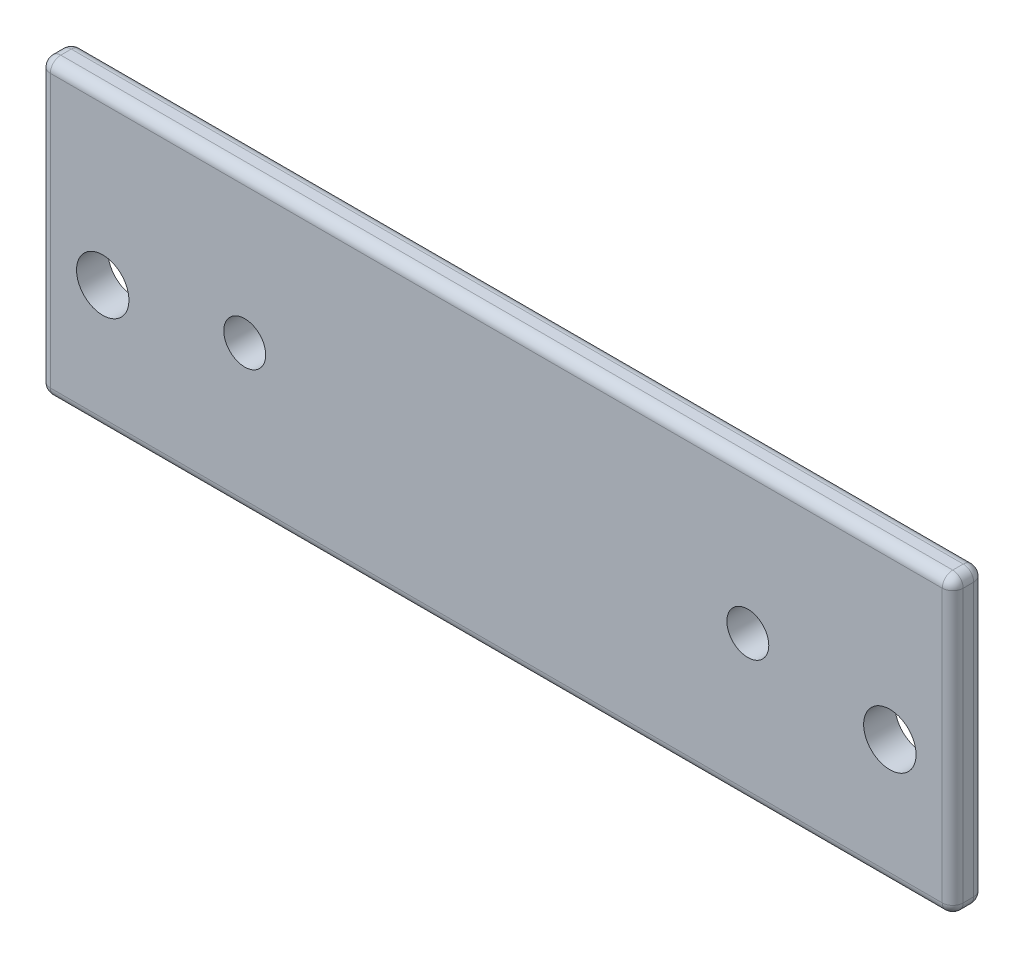
SolidWorks part; units mm, degrees
ref_plane "Front Plane" through (0, 0, 0) normal (0, 0, 1) x (1, 0, 0)
ref_plane "Top Plane" through (0, 0, 0) normal (0, 1, 0) x (1, 0, 0)
ref_plane "Right Plane" through (0, 0, 0) normal (1, 0, 0) x (0, 0, -1)
sketch "Skizze1" plane through (0, 0, 0) normal (0, 0, 1) x (1, 0, 0)
  line L0 (-37.5522, 28) -> (-43.5522, 28)
  line L1 (-37.5522, 28) -> (37.5522, 28)
  line L3 (-37.5522, 0) -> (37.5522, 0)
  line L5 (-43.5522, 28) -> (-43.5522, 0)
  line L6 (-43.5522, 0) -> (-37.5522, 0)
  line L7 (37.5522, 28) -> (43.5522, 28)
  line L8 (43.5522, 28) -> (43.5522, 0)
  line L9 (43.5522, 0) -> (37.5522, 0)
  point P11 (0, 0)
  dimension "D1" = 75.1044
  dimension "D2" = 28
  dimension "D3" = 6
extrude "Aufsatz-Linear austragen1" add sketch "Skizze1" along normal blind 3
sketch "Skizze3" plane through (0, 0, 3) normal (0, 0, 1) x (1, 0, 0)
  line L0 (-37.5522, 28) -> (-37.5522, 12) construction
  line L1 (37.5522, 28) -> (37.5522, 12) construction
  circle A0 centre (-37.5522, 12) radius 2.5
  circle A1 centre (37.5522, 12) radius 2.5
  dimension "D2" = 5
  dimension "D1" = 16
extrude "Schnitt-Linear austragen1" cut sketch "Skizze3" against normal blind 3 contours A0 | A1
sketch "Skizze4" plane through (0, 0, 0) normal (0, 1, 0) x (1, 0, 0)
  line L0 (0, -3) -> (0, -35) construction
  line L1 (43.5522, -3) -> (-43.5522, -3) construction
  line L2 (0, -35) -> (-35, -35) construction
  line L3 (-35, -35) -> (-35, -3) construction
  line L4 (-35, -3) -> (35, -3) construction
  line L5 (35, -3) -> (35, -35) construction
  line L6 (35, -35) -> (0, -35) construction
  line L7 (-24, -19) -> (0, -19) construction
  line L8 (0, -19) -> (24, -19) construction
  circle A0 centre (-24, -19) radius 2
  circle A1 centre (24, -19) radius 2
  dimension "D3" = 4
  dimension "D1" = 70
  dimension "D2" = 32
  dimension "D4" = 24
sketch "Skizze6" plane through (0, 0, 3) normal (0, 0, 1) x (1, 0, 0)
  line L0 (0, 0) -> (0, 28) construction
  line L1 (-37.5522, 0) -> (37.5522, 0) construction
  line L2 (-37.5522, 28) -> (37.5522, 28) construction
  line L3 (0, 14) -> (-24, 14) construction
  line L4 (0, 14) -> (24, 14) construction
  circle A0 centre (-24, 14) radius 2
  circle A1 centre (24, 14) radius 2
  dimension "D1" = 4
  dimension "D2" = 24
extrude "Schnitt-Linear austragen3" cut sketch "Skizze6" against normal up to surface (3 mm away) up to face at (-35.0522, 12, 0)
fillet "Fillet1" radius 1 12 edges at (0, 0, 3) (0, 0, 0) (43.5522, 0, 1.5) (43.5522, 14, 3) (43.5522, 14, 0) (43.5522, 28, 1.5) (0, 28, 3) (0, 28, 0) (-43.5522, 28, 1.5) (-43.5522, 14, 3) (-43.5522, 0, 1.5) (-43.5522, 14, 0)
